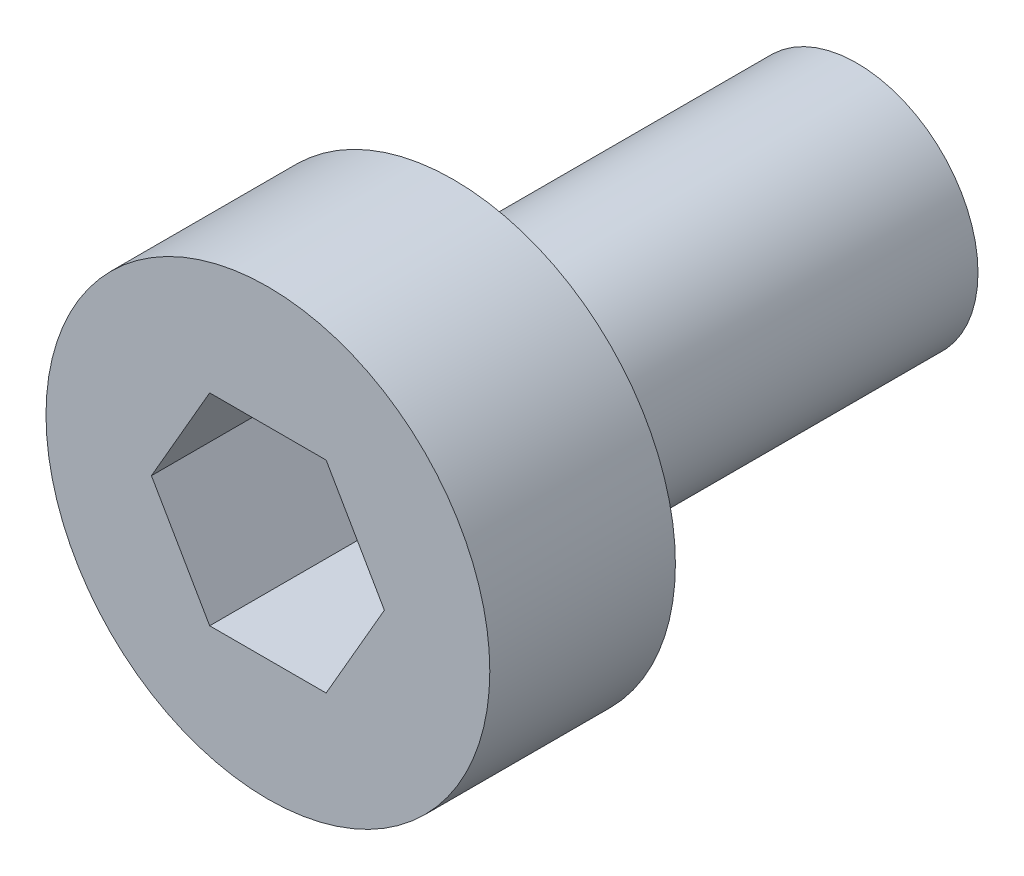
SolidWorks part; units mm, degrees
ref_plane "Plan de face" through (0, 0, 0) normal (0, 0, 1) x (1, 0, 0)
ref_plane "Plan de dessus" through (0, 0, 0) normal (0, 1, 0) x (1, 0, 0)
ref_plane "Plan de droite" through (0, 0, 0) normal (1, 0, 0) x (0, 0, -1)
sketch "Esquisse1" plane through (0, 0, 0) normal (0, 0, 1) x (1, 0, 0)
  circle A0 centre (0, 0) radius 1.5
  dimension "D1" = 3
extrude "Boss.-Extru.1" add sketch "Esquisse1" along normal blind 5
sketch "Esquisse2" plane through (0, 0, 5) normal (0, 0, 1) x (1, 0, 0)
  circle A0 centre (0, 0) radius 2.75
  dimension "D1" = 5.5
extrude "Boss.-Extru.2" add sketch "Esquisse2" along normal blind 2.3
sketch "Esquisse3" plane through (0, 0, 7.3) normal (0, 0, 1) x (1, 0, 0)
  line L1 (1.4434, 0) -> (0.7217, 1.25)
  line L2 (0.7217, 1.25) -> (-0.7217, 1.25)
  line L3 (-0.7217, 1.25) -> (-1.4434, 0)
  line L4 (-1.4434, 0) -> (-0.7217, -1.25)
  line L5 (-0.7217, -1.25) -> (0.7217, -1.25)
  line L6 (0.7217, -1.25) -> (1.4434, 0)
  circle A0 centre (0, 0) radius 1.25 construction
  dimension "D1" = 2.5
extrude "Enlèv. mat.-Extru.1" cut sketch "Esquisse3" against normal blind 2
